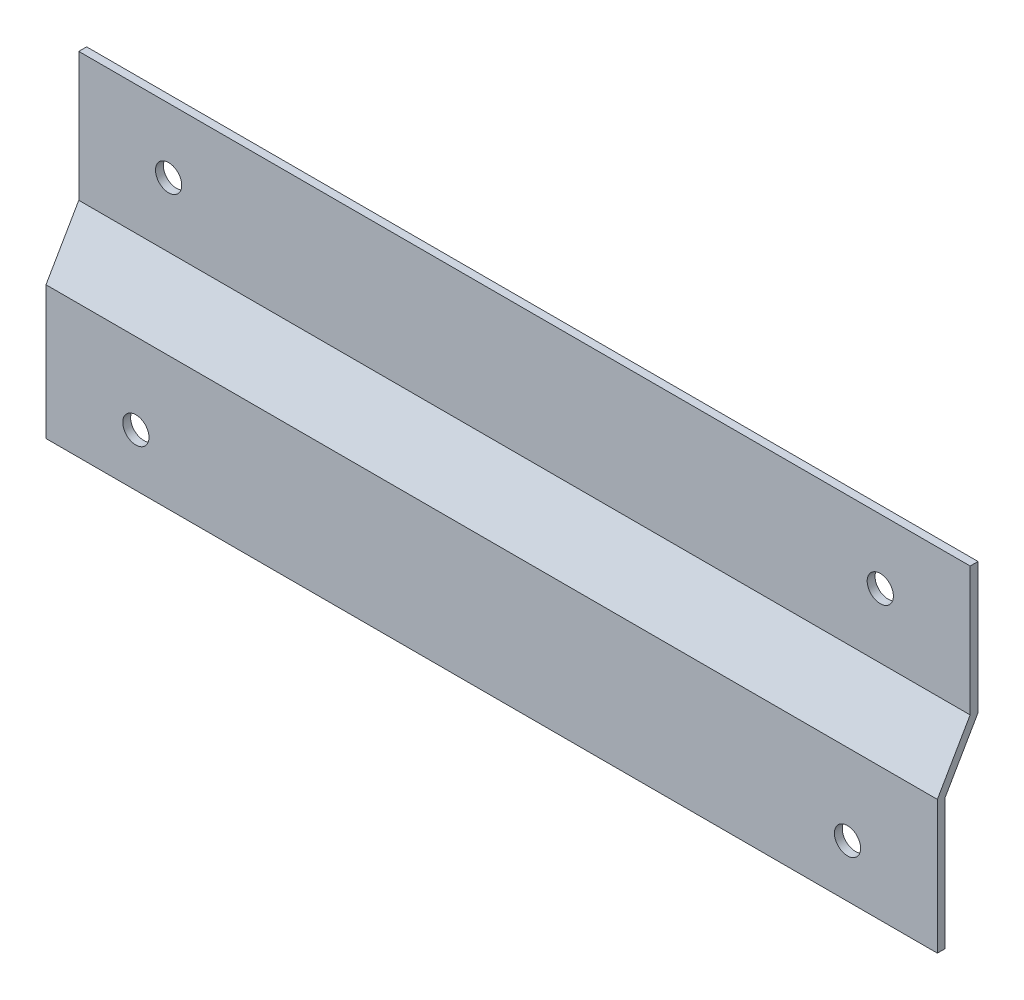
SolidWorks part; units mm, degrees
material "1.4003 (X2CrNi12)"
ref_plane "Płaszczyzna przednia" through (0, 0, 0) normal (0, 0, 1) x (1, 0, 0)
ref_plane "Płaszczyzna górna" through (0, 0, 0) normal (0, 1, 0) x (1, 0, 0)
ref_plane "Płaszczyzna prawa" through (0, 0, 0) normal (1, 0, 0) x (0, 0, -1)
sketch "Szkic2" plane through (0, 0, 0) normal (1, 0, 0) x (0, 0, -1)
  line L0 (0, 50) -> (0, 0)
  line L1 (0, 0) -> (-12.5, -21.6506)
  line L2 (-12.5, -21.6506) -> (-12.5, -71.6506)
  dimension "D1" = 50
  dimension "D2" = 50
  dimension "D3" = 150
  dimension "D4" = 25
extrude "Wyciągnięcie-cienka ścianka2" add sketch "Szkic2" along normal blind 170 and the other way blind 170 thin
sketch "Szkic3" plane through (0, 0, 3) normal (0, 0, 1) x (1, 0, 0)
  line L0 (0, 90.0259) -> (0, -133.3895) construction
  line L1 (-170, -71.6506) -> (170, -71.6506) construction
  line L3 (-170, 50) -> (-170, 0.8038) construction
  circle A0 centre (-135.725, 25.4019) radius 5
  circle A1 centre (-135.725, -51.6506) radius 5
  point P9 (0, 0)
  point P10 (0, 0)
  point P11 (0, 0)
  point P14 (0, 0)
  point P15 (-170, 25.4019)
  dimension "D1" = 10
  dimension "D2" = 10
  dimension "D3" = 271.45
  dimension "D4" = 20
extrude "Wytnij-wyciągnięcie2" cut sketch "Szkic3" against normal blind 10 and the other way blind 40
mirror "Lustro1" about plane through (0, 0, 0) normal (1, 0, 0) of "Wytnij-wyciągnięcie2"
